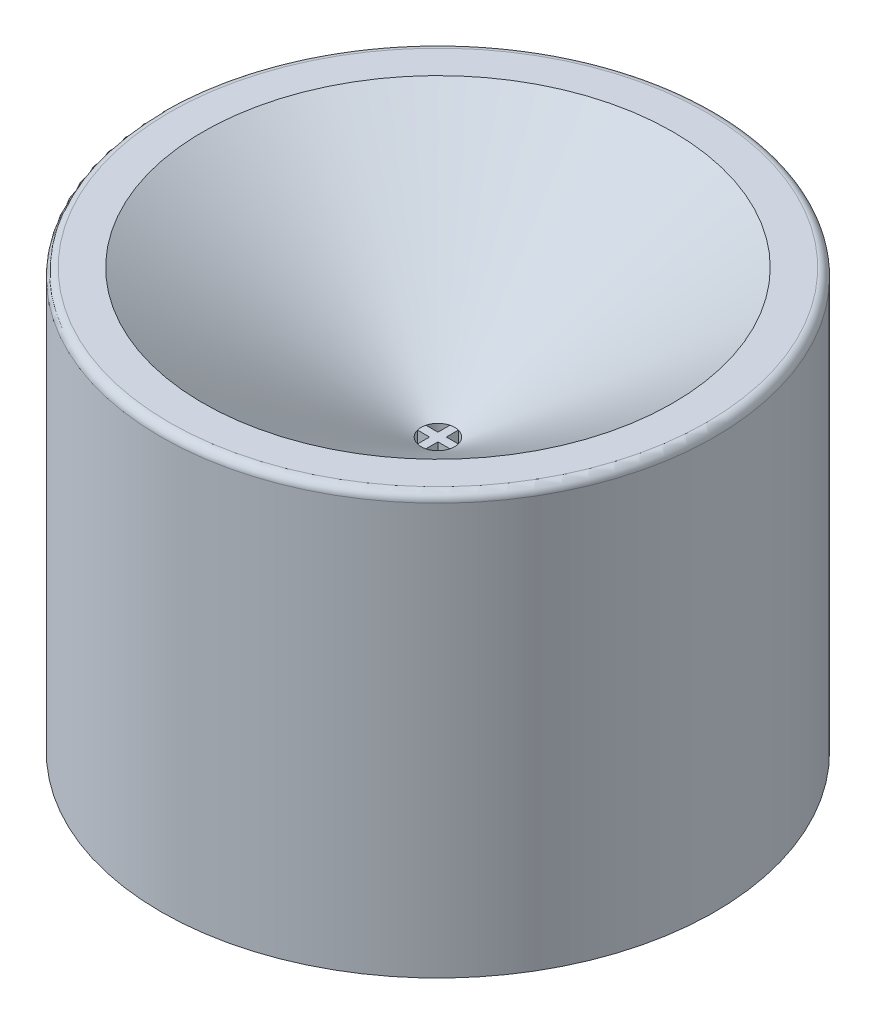
SolidWorks part; units mm, degrees
ref_plane "Front Plane" through (0, 0, 0) normal (0, 0, 1) x (1, 0, 0)
ref_plane "Top Plane" through (0, 0, 0) normal (0, 1, 0) x (1, 0, 0)
ref_plane "Right Plane" through (0, 0, 0) normal (1, 0, 0) x (0, 0, -1)
sketch "Sketch1" plane through (0, 0, 0) normal (0, 1, 0) x (1, 0, 0)
  circle A0 centre (0, 0) radius 83.82
  dimension "D1" = 167.64
extrude "Boss-Extrude1" add sketch "Sketch1" along normal blind 127 contours A0
sketch "Sketch2" plane through (0, 0, 0) normal (0, 0, 1) x (1, 0, 0)
  line L0 (0, 0) -> (0, 127) construction
  line L1 (83.82, 127) -> (-83.82, 127) construction
  line L2 (-5.08, 82.55) -> (0, 82.55)
  line L3 (-5.08, 82.55) -> (-71.12, 127)
  line L4 (-83.82, 127) -> (-83.82, 0) construction
  line L5 (0, 82.55) -> (0, 127)
  line L6 (0, 127) -> (-71.12, 127)
  dimension "D1" = 12.7
  dimension "D2" = 5.08
  dimension "D3" = 44.45
revolve "Cut-Revolve1" cut sketch "Sketch2" angle 360 about L0
shell "Shell1" thickness 6.35
sketch "Sketch4" plane through (0, 82.55, 0) normal (0, 1, 0) x (1, 0, 0)
  line L0 (0, 5.08) -> (0, -5.08) construction
  line L1 (-5.08, 0) -> (5.08, 0) construction
  line L2 (-1.27, 5.08) -> (-1.27, -5.08)
  line L3 (-5.08, -1.27) -> (5.08, -1.27)
  line L4 (1.27, 5.08) -> (1.27, -5.08)
  line L5 (-5.08, 1.27) -> (5.08, 1.27)
  circle A0 centre (0, 0) radius 5.08 construction
  circle A1 centre (0, 0) radius 5.2363
  circle M5 centre (0, 0) radius 5.08
  dimension "D1" = 1.27
  dimension "D2" = 1.27
extrude "Cut-Extrude2" cut sketch "Sketch4" against normal up to next contours L5 L2 M5 | L4 L5 M5 | L3 L2 M5 | L3 L4 M5
fillet "Fillet2" radius 2.54 1 edges at (0, 127, 83.82)
